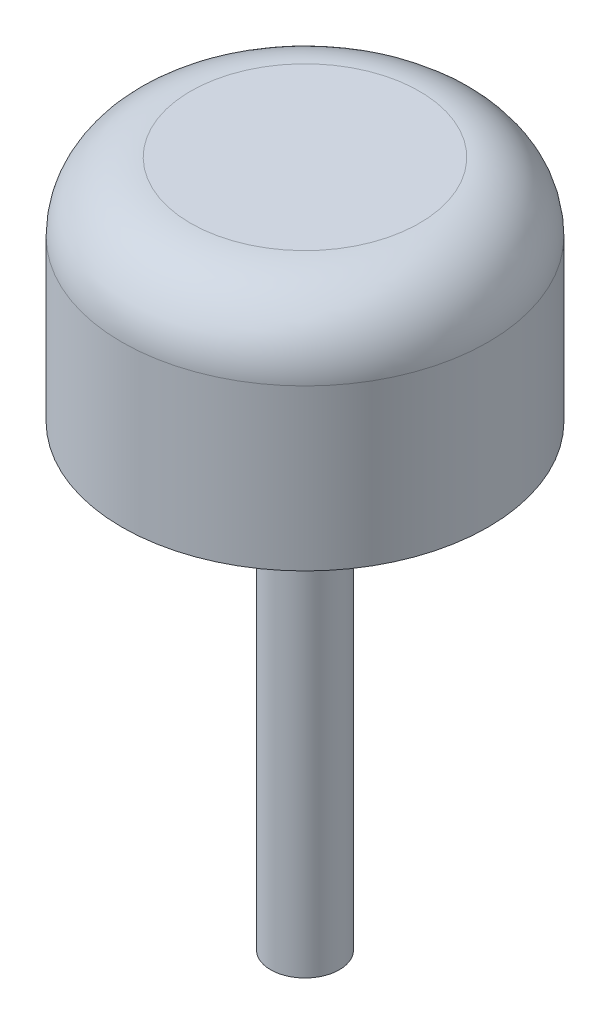
SolidWorks part; units mm, degrees
material "Thornel Mat VMA"
ref_plane "前视" through (0, 0, 0) normal (0, 0, 1) x (1, 0, 0)
ref_plane "上视" through (0, 0, 0) normal (0, 1, 0) x (1, 0, 0)
ref_plane "右视" through (0, 0, 0) normal (1, 0, 0) x (0, 0, -1)
sketch "草图1" plane through (0, 0, 0) normal (0, 1, 0) x (1, 0, 0)
  circle A0 centre (0, 0) radius 8
extrude "凸台-拉伸1" add sketch "草图1" along normal blind 10
sketch "草图2" plane through (0, 0, 0) normal (0, -1, 0) x (1, 0, 0)
  circle A0 centre (0, 0) radius 1.5
extrude "凸台-拉伸2" add sketch "草图2" along normal blind 20
fillet "圆角2" radius 3 1 edges at (0, 10, 8)
